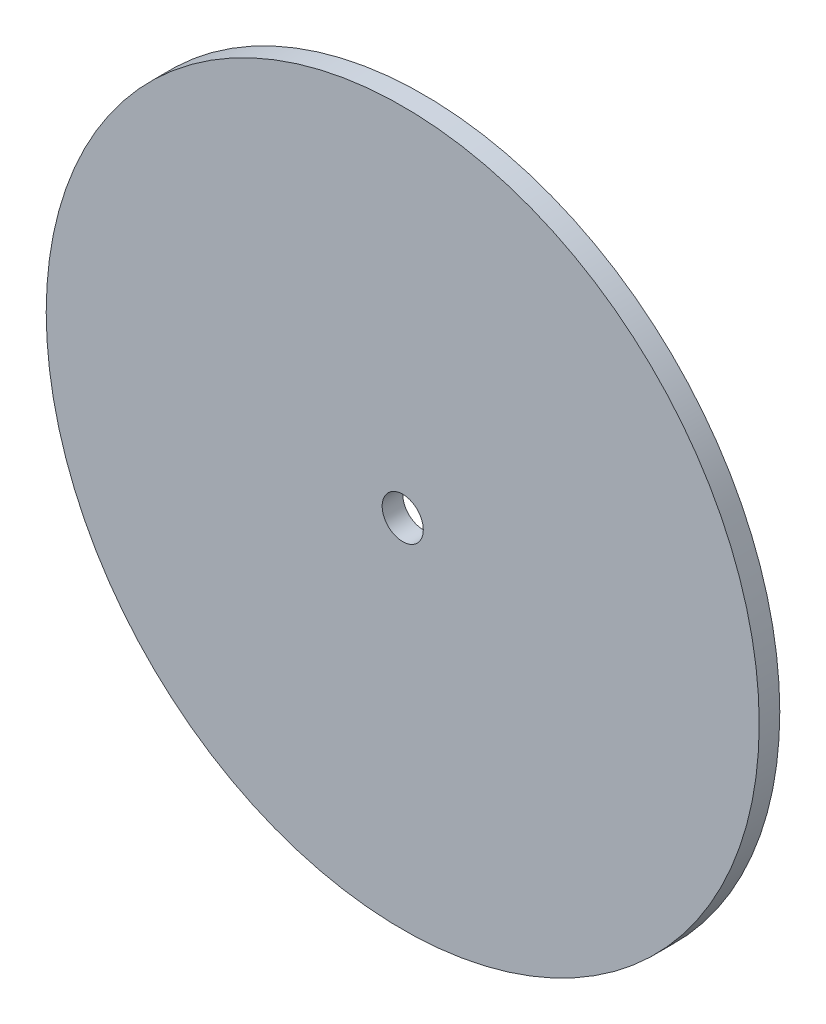
SolidWorks part; units mm, degrees
ref_plane "前视基准面" through (0, 0, 0) normal (0, 0, 1) x (1, 0, 0)
ref_plane "上视基准面" through (0, 0, 0) normal (0, 1, 0) x (1, 0, 0)
ref_plane "右视基准面" through (0, 0, 0) normal (1, 0, 0) x (0, 0, -1)
other "Configuration Table"
sketch "草图1" plane through (0, 0, 0) normal (0, 0, 1) x (1, 0, 0)
  circle A0 centre (0, 0) radius 52
  circle A1 centre (0, 0) radius 3
  dimension "D1" = 104
  dimension "D2" = 6
extrude "凸台-拉伸1" add sketch "草图1" along normal blind 3 contours A0 A1
